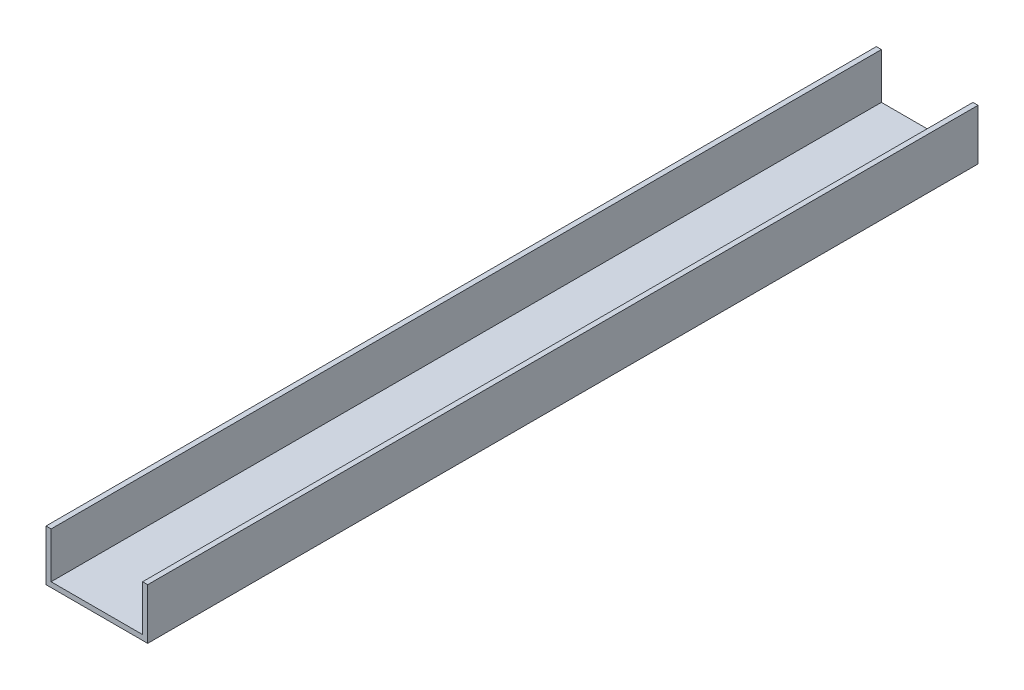
SolidWorks part; units mm, degrees
ref_plane "Piano frontale" through (0, 0, 0) normal (0, 0, 1) x (1, 0, 0)
ref_plane "Piano superiore" through (0, 0, 0) normal (0, 1, 0) x (1, 0, 0)
ref_plane "Piano destro" through (0, 0, 0) normal (1, 0, 0) x (0, 0, -1)
sketch "Schizzo1" plane through (0, 0, 0) normal (0, 0, 1) x (1, 0, 0)
  line L0 (-22.9867, -3.314) -> (37.0133, -3.314)
  line L1 (37.0133, -3.314) -> (37.0133, 26.686)
  line L2 (37.0133, 26.686) -> (34.0133, 26.686)
  line L3 (34.0133, 26.686) -> (34.0133, -0.314)
  line L4 (34.0133, -0.314) -> (-19.9867, -0.314)
  line L5 (-19.9867, -0.314) -> (-19.9867, 26.686)
  line L6 (-19.9867, 26.686) -> (-22.9867, 26.686)
  line L7 (-22.9867, 26.686) -> (-22.9867, -3.314)
  point P5 (-19.9867, 13.186)
  dimension "D1" = 60
  dimension "D2" = 30
  dimension "D3" = 3
  dimension "D4" = 3
extrude "Estrusione-Estrusione1" add sketch "Schizzo1" along normal blind 490
